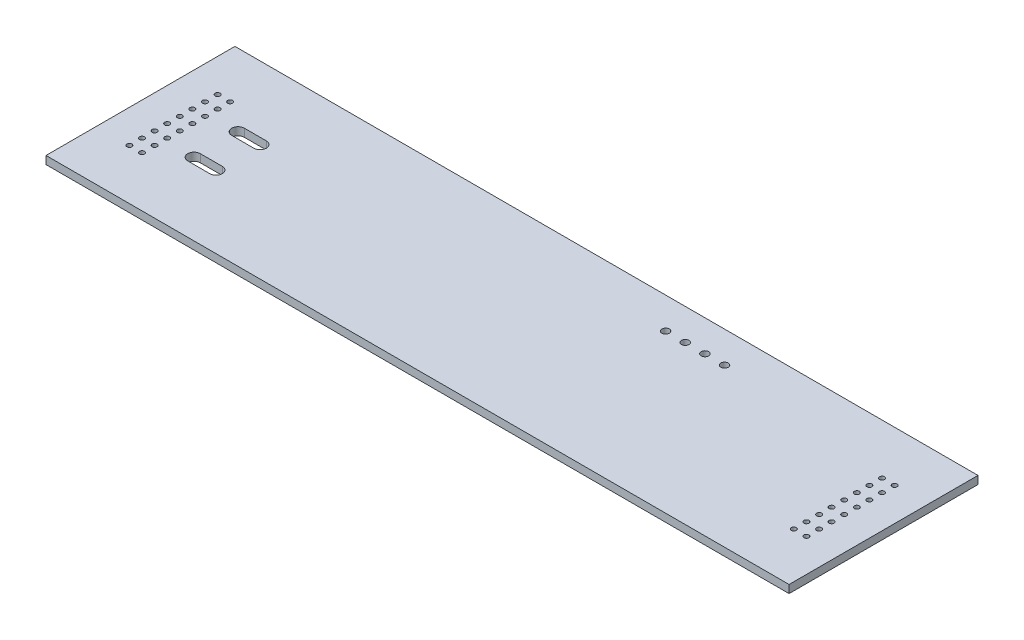
SolidWorks part; units mm, degrees
ref_plane "Front Plane" through (0, 0, 0) normal (0, 0, 1) x (1, 0, 0)
ref_plane "Top Plane" through (0, 0, 0) normal (0, 1, 0) x (1, 0, 0)
ref_plane "Right Plane" through (0, 0, 0) normal (1, 0, 0) x (0, 0, -1)
sketch "Sketch1" plane through (0, 27.9329, 0) normal (0, 1, 0) x (1, 0, 0)
  line L1 (-74.93, -19.05) -> (74.93, -19.05)
  line L2 (-74.93, -19.05) -> (-74.93, 19.05)
  line L3 (-74.93, 19.05) -> (74.93, 19.05)
  line L4 (74.93, -19.05) -> (74.93, 19.05)
  line L5 (-74.93, -19.05) -> (74.93, 19.05) construction
  line L6 (-74.93, 19.05) -> (74.93, -19.05) construction
  point P0 (0, 0)
  dimension "D1" = 149.86
  dimension "D2" = 38.1
extrude "Boss-Extrude1" add sketch "Sketch1" along normal blind 1.6
sketch "Sketch7" plane through (0, 29.5329, 0) normal (0, 1, 0) x (1, 0, 0)
  line L0 (29.23, 13.25) -> (29.23, 12.25) construction
  line L1 (29.23, 12.25) -> (30.23, 12.25) construction
  line L2 (30.23, 12.25) -> (30.23, 13.25) construction
  line L3 (30.23, 13.25) -> (29.23, 13.25) construction
  line L4 (-67.945, 8.565) -> (-67.945, 9.215)
  line L5 (-67.945, 9.215) -> (-68.595, 9.215)
  line L6 (-68.595, 9.215) -> (-68.595, 8.565)
  line L7 (-68.595, 8.565) -> (-67.945, 8.565)
  line L8 (-67.945, 8.565) -> (-67.945, 9.215)
  line L9 (-67.945, 9.215) -> (-68.595, 9.215)
  line L10 (-68.595, 9.215) -> (-68.595, 8.565)
  line L11 (-68.595, 8.565) -> (-67.945, 8.565)
  line L12 (17.73, 13.25) -> (17.73, 12.25) construction
  line L13 (17.73, 12.25) -> (18.73, 12.25) construction
  line L14 (18.73, 12.25) -> (18.73, 13.25) construction
  line L15 (18.73, 13.25) -> (17.73, 13.25) construction
  line L16 (29.23, 13.25) -> (29.23, 12.25)
  line L17 (29.23, 12.25) -> (30.23, 12.25)
  line L18 (30.23, 12.25) -> (30.23, 13.25)
  line L19 (30.23, 13.25) -> (29.23, 13.25)
  line L20 (17.73, 13.25) -> (17.73, 12.25)
  line L21 (17.73, 12.25) -> (18.73, 12.25)
  line L22 (18.73, 12.25) -> (18.73, 13.25)
  line L23 (18.73, 13.25) -> (17.73, 13.25)
  line L24 (66.055, 8.565) -> (65.405, 9.215) construction
  line L25 (30.23, 12.25) -> (29.23, 13.25) construction
  line L26 (18.73, 12.25) -> (17.73, 13.25) construction
  line L27 (-67.945, 8.565) -> (-68.595, 9.215) construction
  line L28 (66.055, 8.565) -> (66.055, 9.215)
  line L29 (66.055, 9.215) -> (65.405, 9.215)
  line L30 (65.405, 9.215) -> (65.405, 8.565)
  line L31 (65.405, 8.565) -> (66.055, 8.565)
  line L32 (66.055, 8.565) -> (66.055, 9.215)
  line L33 (66.055, 9.215) -> (65.405, 9.215)
  line L34 (65.405, 9.215) -> (65.405, 8.565)
  line L35 (65.405, 8.565) -> (66.055, 8.565)
  line L1260 (29.73, 12.75) -> (18.23, 12.75) construction
  point P0 (65.73, 8.89)
  point P1 (18.23, 12.75)
  point P2 (29.73, 12.75)
  point P3 (-68.27, 8.89)
  point P14 (23.98, 12.75)
  point P18 (0, 0)
  point P22 (0, 0)
  dimension "D3" = 86.5
  dimension "D1" = 0
  dimension "D2" = 0
hole_wizard "Ø1.0mm Dowel Hole1" positions "3DSketch1" profile "Sketch4" hole size "Ø1.0" standard "ANSI Metric" end condition through all
sketch3d "3DSketch1"
  point P6 (65.73, 29.5329, -8.89)
  point P13 (-68.27, 29.5329, -8.89)
sketch "Sketch4" plane through (65.73, 29.5329, -8.89) normal (1, 0, 0) x (0, 0, 1)
  line L0 (0, 0) -> (0, 1.6)
  line L1 (0, 1.6) -> (0.5, 1.6)
  line L2 (0.5, 1.6) -> (0.5, 0)
  line L5 (0.5, 0) -> (0, 0)
  line L11 (0, -6.35) -> (0, 107.95) construction
  dimension "Thru Hole Dia." = 1
  dimension "Thru Hole Depth" = 1.6
pattern_linear "LPattern1" count 2 spacing 2.54 along (1, 0, 0) count 8 spacing 2.54 along (0, 0, 1) of "Ø1.0mm Dowel Hole1"
hole_wizard "Ø1.5mm Dowel Hole1" positions "3DSketch2" profile "Sketch5" hole size "Ø1.5" standard "ANSI Metric" end condition up to next
sketch3d "3DSketch2"
  point P3 (18.23, 29.5329, -12.75)
sketch "Sketch5" plane through (18.23, 29.5329, -12.75) normal (1, 0, 0) x (0, 0, 1)
  line L0 (0, 0) -> (0, 1.6)
  line L1 (0, 1.6) -> (0.75, 1.6)
  line L2 (0.75, 1.6) -> (0.75, 0)
  line L5 (0.75, 0) -> (0, 0)
  line L11 (0, -6.35) -> (0, 107.95) construction
  dimension "Thru Hole Dia." = 1.5
  dimension "Thru Hole Depth" = 1.6
pattern_linear "LPattern2" count 4 spacing 3.96 along (1, 0, 0) of "Ø1.5mm Dowel Hole1"
sketch "Sketch6" plane through (0, 29.5329, 0) normal (0, 1, 0) x (1, 0, 0)
  line L0 (-55.245, -4.445) -> (-59.69, -4.445) construction
  line L1 (-55.245, -5.715) -> (-59.69, -5.715)
  line L2 (-55.245, -3.175) -> (-59.69, -3.175)
  line L3 (-0.88, 0) -> (0.88, 0) construction
  line L4 (-55.245, 4.445) -> (-59.69, 4.445) construction
  line L5 (-55.245, 5.715) -> (-59.69, 5.715)
  line L6 (-55.245, 3.175) -> (-59.69, 3.175)
  line L7 (-74.93, 19.05) -> (-74.93, -19.05) construction
  arc A0 (-55.245, -5.715) -> (-55.245, -3.175) centre (-55.245, -4.445) ccw
  arc A1 (-59.69, -3.175) -> (-59.69, -5.715) centre (-59.69, -4.445) ccw
  arc A2 (-55.245, 5.715) -> (-55.245, 3.175) centre (-55.245, 4.445) cw
  arc A3 (-59.69, 3.175) -> (-59.69, 5.715) centre (-59.69, 4.445) cw
  point P2 (-57.4675, -4.445)
  point P11 (-57.4675, 4.445)
  dimension "D1" = 4.445
  dimension "D2" = 2.54
  dimension "D3" = 8.89
  dimension "D4" = 15.24
extrude "Cut-Extrude1" cut sketch "Sketch6" against normal through all
sketch "Sketch8" plane through (0, 29.5329, 0) normal (0, 1, 0) x (1, 0, 0)
  point P0 (-65.73, 8.89)
